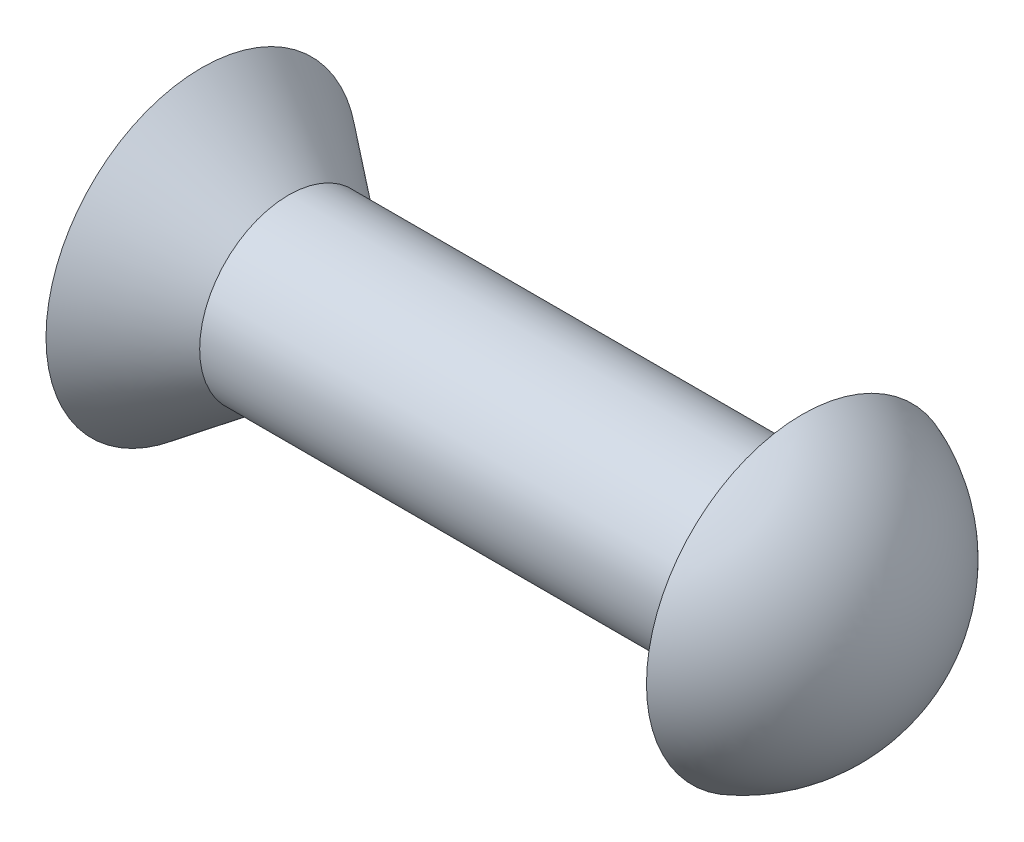
SolidWorks part; units mm, degrees
ref_plane "Plane1" through (0, 0, 0) normal (0, 0, 1) x (1, 0, 0)
ref_plane "Plane2" through (0, 0, 0) normal (0, 1, 0) x (1, 0, 0)
ref_plane "Plane3" through (0, 0, 0) normal (1, 0, 0) x (0, 0, -1)
sketch "Sketch1" plane through (0, 0, 0) normal (0, 0, 1) x (1, 0, 0)
  line L0 (-34, 0) -> (6, 0) construction
  line L1 (-27, 0) -> (0, 0)
  line L2 (0, 4) -> (-23.0903, 4)
  line L3 (-23.0903, 4) -> (-27, 7)
  line L4 (0, 4) -> (0, 0)
  line L5 (-27, 7) -> (-27, 0)
  line L6 (-23.0903, -4) -> (-27, -7) construction
  dimension "HeadDia" = 14
  dimension "D1" = 75
  dimension "GripLength" = 27
  dimension "Diameter" = 8
revolve "Base-Revolve" add sketch "Sketch1" angle 360 about L0
sketch "Sketch2" plane through (0, 0, 0) normal (0, 0, 1) x (1, 0, 0)
  line L0 (-32, 0) -> (8, 0) construction
  line L1 (0, 0) -> (4.8, 0)
  line L2 (0, 0) -> (0, 7)
  arc A0 (4.8, 0) -> (0, 7) centre (-2.7, 0.0029) ccw
  dimension "HeadRad" = 7.5
  dimension "D1" = 14
  dimension "HeadHt" = 4.8
revolve "HeadTypeA" add sketch "Sketch2" angle 360 about L0
sketch "Sketch3" plane through (0, 0, 0) normal (0, 0, 1) x (1, 0, 0)
  line L0 (3, 0) -> (-30, 0) construction
  line L1 (-34, 0) -> (6, 0) construction
  line L2 (0, 0) -> (0, 7)
  line L3 (0, 7) -> (-3.9097, 4)
  line L4 (-3.9097, 0) -> (0, 0)
  line L5 (0, -7) -> (-3.9097, -4) construction
  line L9 (-3.9097, 4) -> (-3.9097, 0)
  dimension "D2" = 75
  dimension "D3" = 14
  dimension "D1" = 8
revolve "HeadTypeB" [suppressed] add sketch "Sketch3" angle 360 about L0
equation "\"D1@Sketch2\" = \"HeadDia@Sketch1\""
equation "\"D3@Sketch3\" = \"HeadDia@Sketch1\""
equation "\"D1@Sketch3\" = \"Diameter@Sketch1\""
